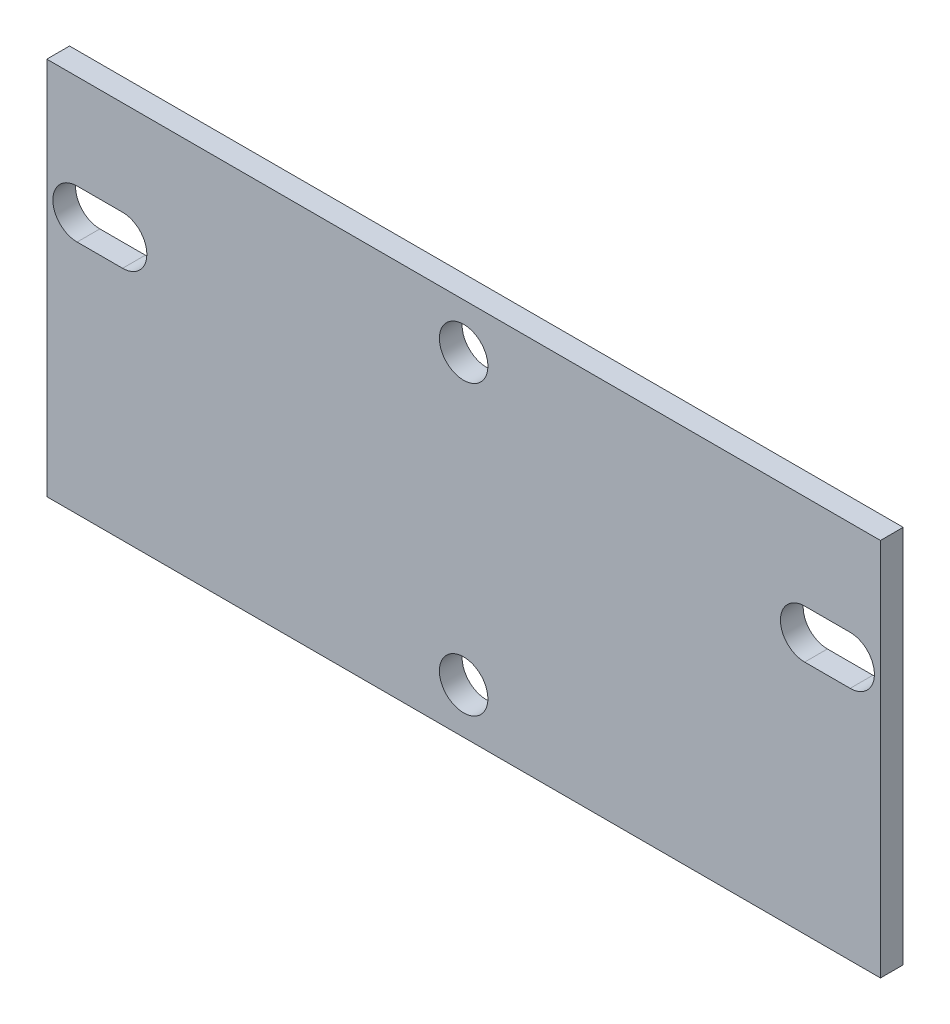
SolidWorks part; units mm, degrees
ref_plane "Спереди" through (0, 0, 0) normal (0, 0, 1) x (1, 0, 0)
ref_plane "Сверху" through (0, 0, 0) normal (0, 1, 0) x (1, 0, 0)
ref_plane "Справа" through (0, 0, 0) normal (1, 0, 0) x (0, 0, -1)
sketch "Эскиз1" plane through (0, 0, 0) normal (0, 0, 1) x (1, 0, 0)
  line L1 (0, 0) -> (55, 0)
  line L2 (0, 0) -> (0, 25)
  line L3 (0, 25) -> (55, 25)
  line L4 (55, 0) -> (55, 25)
  dimension "D1" = 55
  dimension "D2" = 25
extrude "Бобышка-Вытянуть1" add sketch "Эскиз1" along normal blind 1.5
sketch "Эскиз2" plane through (0, 0, 1.5) normal (0, 0, 1) x (1, 0, 0)
  line L0 (2, 17.15) -> (5, 17.15) construction
  line L1 (2, 18.75) -> (5, 18.75)
  line L2 (2, 15.55) -> (5, 15.55)
  line L3 (0, 25) -> (0, 0) construction
  line L4 (27.5, 25) -> (27.5, 0) construction
  line L5 (55, 25) -> (0, 25) construction
  line L6 (0, 0) -> (55, 0) construction
  line L7 (53, 17.15) -> (50, 17.15) construction
  line L8 (53, 18.75) -> (50, 18.75)
  line L9 (53, 15.55) -> (50, 15.55)
  arc A0 (2, 18.75) -> (2, 15.55) centre (2, 17.15) ccw
  arc A1 (5, 15.55) -> (5, 18.75) centre (5, 17.15) ccw
  arc A2 (53, 18.75) -> (53, 15.55) centre (53, 17.15) cw
  arc A3 (50, 15.55) -> (50, 18.75) centre (50, 17.15) cw
  point P2 (3.5, 17.15)
  point P9 (0, 12.5)
  point P18 (51.5, 17.15)
  dimension "D1" = 4.65
  dimension "D2" = 3.2
  dimension "D3" = 24
  dimension "D4" = 3
extrude "Вырез-Вытянуть1" cut sketch "Эскиз2" against normal through all
sketch "Эскиз3" plane through (0, 0, 1.5) normal (0, 0, 1) x (1, 0, 0)
  line L0 (27.5, 25) -> (27.5, 0) construction
  line L1 (55, 25) -> (0, 25) construction
  line L2 (0, 0) -> (55, 0) construction
  line L3 (55, 0) -> (55, 25) construction
  circle A0 centre (27.5, 22) radius 1.6
  circle A1 centre (27.5, 3) radius 1.6
  point P12 (55, 12.5)
  dimension "D1" = 3.2
  dimension "D2" = 19
  dimension "D3" = 9.5
extrude "Вырез-Вытянуть2" cut sketch "Эскиз3" against normal through all
sketch "Эскиз4" plane through (0, 0, 0) normal (0, 0, -1) x (-1, 0, 0)
  line L0 (-30, 22) -> (-25, 22) construction
  line L1 (-30, 23.6) -> (-25, 23.6)
  line L2 (-30, 20.4) -> (-25, 20.4)
  line L3 (-55, 12.5) -> (0, 12.5) construction
  line L4 (-55, 0) -> (-55, 25) construction
  line L5 (0, 25) -> (0, 0) construction
  line L6 (-30, 3) -> (-25, 3) construction
  line L7 (-30, 1.4) -> (-25, 1.4)
  line L8 (-30, 4.6) -> (-25, 4.6)
  arc A0 (-30, 23.6) -> (-30, 20.4) centre (-30, 22) ccw
  arc A1 (-25, 20.4) -> (-25, 23.6) centre (-25, 22) ccw
  arc A2 (-30, 1.4) -> (-30, 4.6) centre (-30, 3) cw
  arc A3 (-25, 4.6) -> (-25, 1.4) centre (-25, 3) cw
  point P2 (-27.5, 22)
  point P16 (-27.5, 3)
  dimension "D2" = 3.2
  dimension "D1" = 3.2
  dimension "D3" = 5
extrude "Вырез-Вытянуть3" [suppressed] cut sketch "Эскиз4" against normal through all
